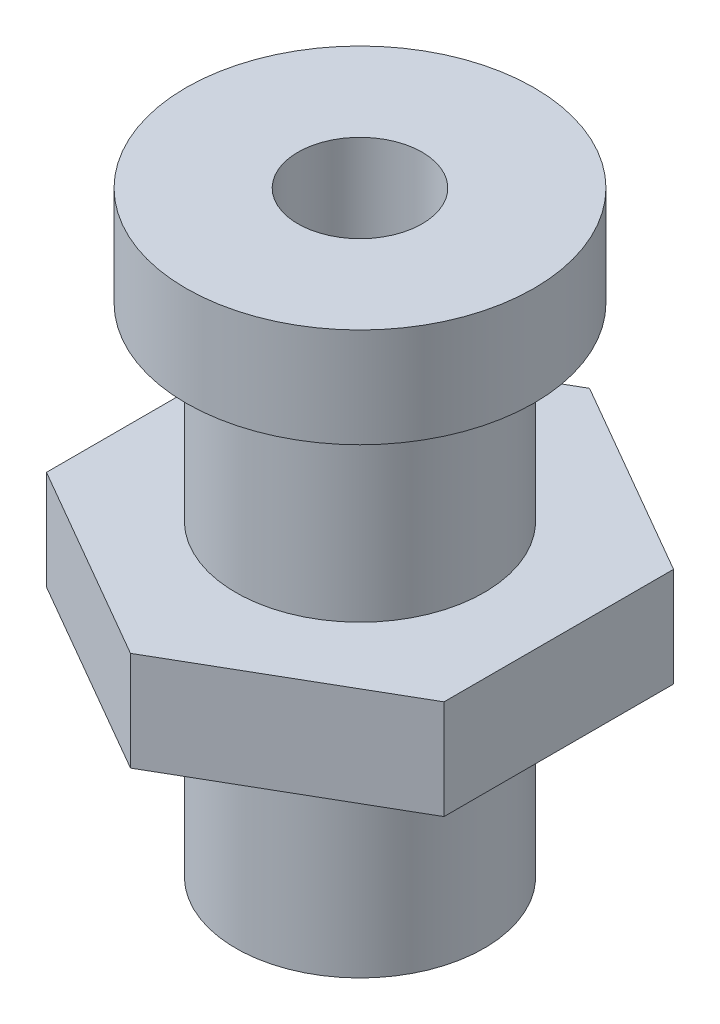
SolidWorks part; units mm, degrees
ref_plane "Front" through (0, 0, 0) normal (0, 0, 1) x (1, 0, 0)
ref_plane "Top" through (0, 0, 0) normal (0, 1, 0) x (1, 0, 0)
ref_plane "Right" through (0, 0, 0) normal (1, 0, 0) x (0, 0, -1)
sketch "Esquisse1" plane through (0, 0, 0) normal (0, 0, 1) x (1, 0, 0)
  line L0 (1.25, 0) -> (1.25, 5.8)
  line L1 (1.25, 5.8) -> (3.5, 5.8)
  line L2 (3.5, 5.8) -> (3.5, 3.8)
  line L3 (3.5, 3.8) -> (2.5, 3.8)
  line L4 (2.5, 3.8) -> (2.5, 0)
  line L5 (2.5, 0) -> (1.25, 0)
  line L6 (0, 0) -> (0, 5.8) construction
  dimension "D1" = 2
  dimension "D2" = 3.8
  dimension "D3" = 7
  dimension "D4" = 5
  dimension "D5" = 2.5
revolve "Révolution1" add sketch "Esquisse1" angle 360 about L6
sketch "Esquisse2" plane through (0, 0, 0) normal (0, -1, 0) x (1, 0, 0)
  line L1 (4, 2.3094) -> (0, 4.6188)
  line L2 (0, 4.6188) -> (-4, 2.3094)
  line L3 (-4, 2.3094) -> (-4, -2.3094)
  line L4 (-4, -2.3094) -> (0, -4.6188)
  line L5 (0, -4.6188) -> (4, -2.3094)
  line L6 (4, -2.3094) -> (4, 2.3094)
  circle A0 centre (0, 0) radius 4 construction
  circle A1 centre (0, 0) radius 1.25 construction
  circle A2 centre (0, 0) radius 1.25
  dimension "D1" = 8
extrude "Boss.-Extru.1" add sketch "Esquisse2" along normal blind 2
sketch "Esquisse3" plane through (0, -2, 0) normal (0, -1, 0) x (1, 0, 0)
  circle A0 centre (0, 0) radius 2.5
  circle A1 centre (0, 0) radius 1.25 construction
  circle A2 centre (0, 0) radius 1.25
  dimension "D1" = 5
extrude "Boss.-Extru.2" add sketch "Esquisse3" along normal blind 4.2
